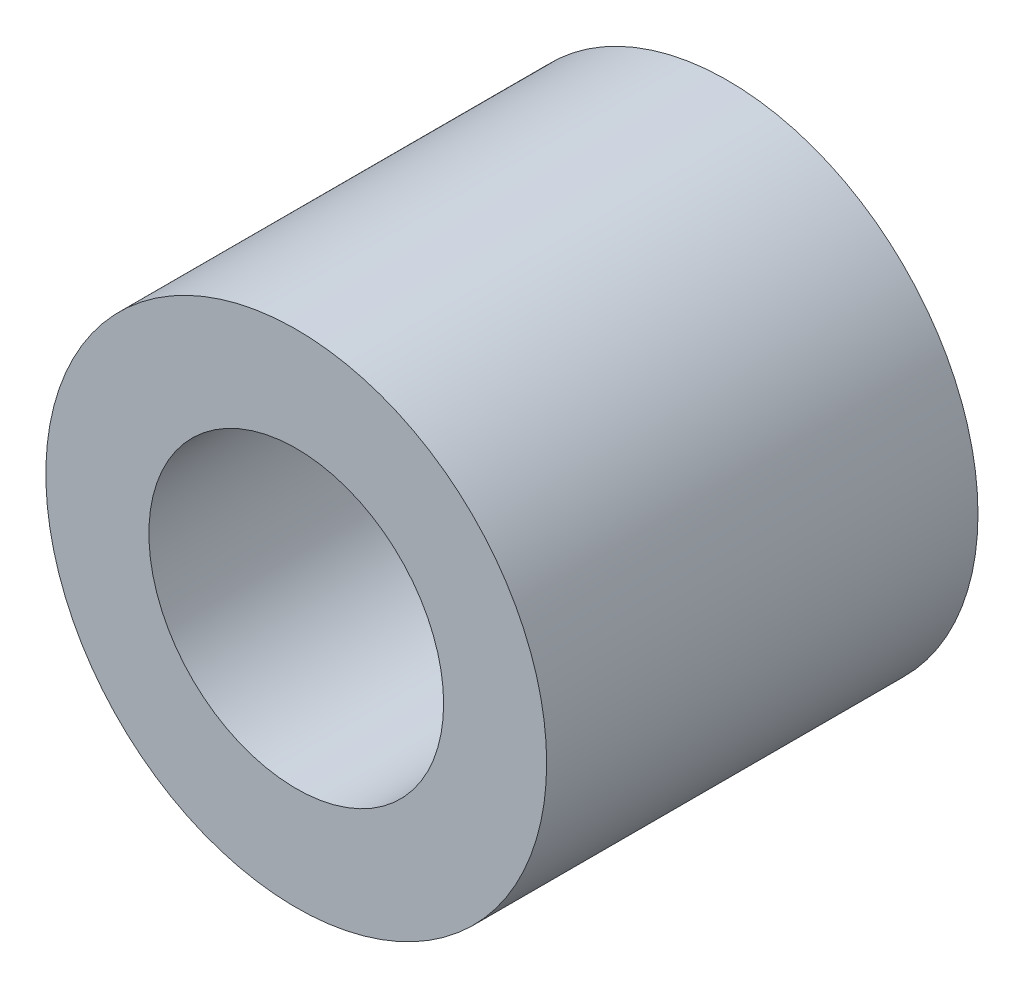
SolidWorks part; units mm, degrees
ref_plane "Front Plane" through (0, 0, 0) normal (0, 0, 1) x (1, 0, 0)
ref_plane "Top Plane" through (0, 0, 0) normal (0, 1, 0) x (1, 0, 0)
ref_plane "Right Plane" through (0, 0, 0) normal (1, 0, 0) x (0, 0, -1)
sketch "Sketch1" plane through (0, 0, 0) normal (0, 0, 1) x (1, 0, 0)
  circle A0 centre (0, 0) radius 10.45
  circle A1 centre (0, 0) radius 6.15
  dimension "D1" = 20.9
  dimension "D2" = 12.3
extrude "Boss-Extrude1" add sketch "Sketch1" along normal blind 18
